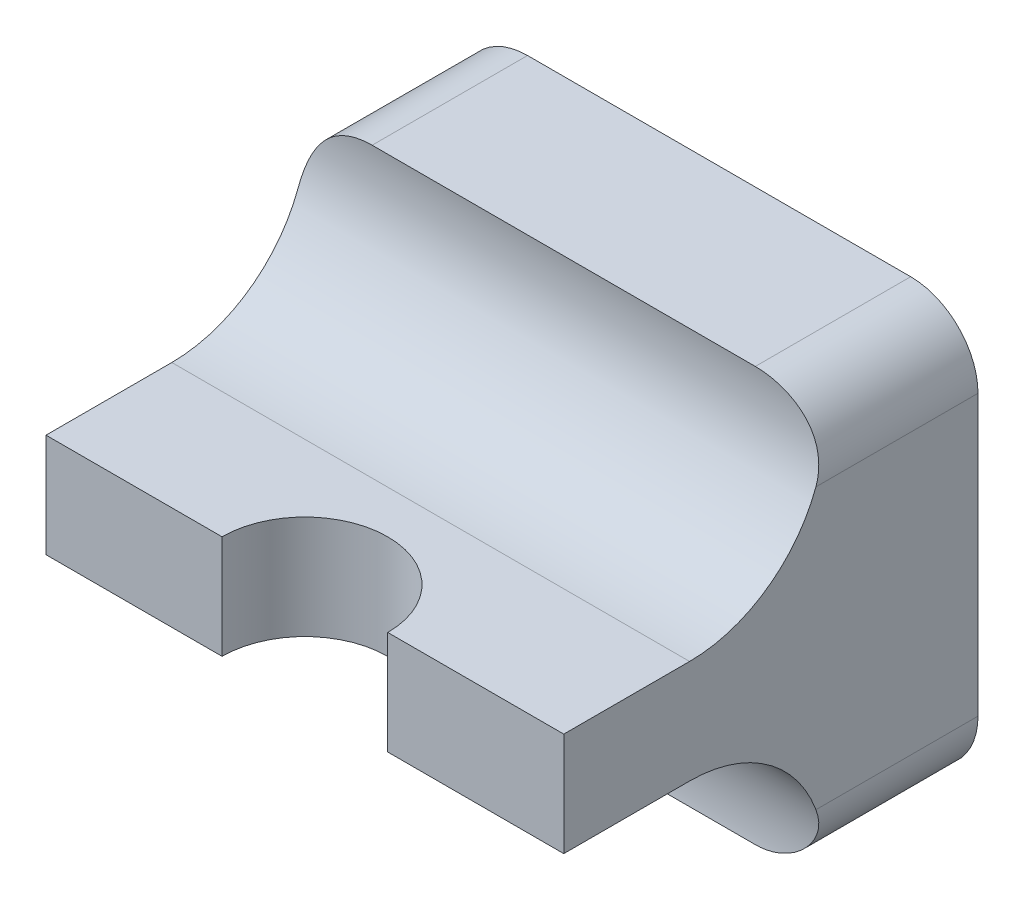
SolidWorks part; units mm, degrees
ref_plane "Front Plane" through (0, 0, 0) normal (0, 0, 1) x (1, 0, 0)
ref_plane "Top Plane" through (0, 0, 0) normal (0, 1, 0) x (1, 0, 0)
ref_plane "Right Plane" through (0, 0, 0) normal (1, 0, 0) x (0, 0, -1)
sketch "Sketch1" plane through (0, 0, 0) normal (0, 0, 1) x (1, 0, 0)
  line L9 (-37, -6.5) -> (0, -6.5)
  line L10 (-43.5, 0) -> (-43.5, 27)
  line L11 (-37, 33.5) -> (0, 33.5)
  line L12 (6.5, 0) -> (6.5, 27)
  arc A4 (-37, 33.5) -> (-43.5, 27) centre (-37, 27) ccw
  arc A5 (-43.5, 0) -> (-37, -6.5) centre (-37, 0) ccw
  arc A6 (0, -6.5) -> (6.5, 0) centre (0, 0) ccw
  arc A7 (6.5, 27) -> (0, 33.5) centre (0, 27) ccw
  point P3 (0, 0)
  point P4 (-43.5, 7.2576)
  point P12 (-7.3381, 33.5)
  point P13 (-6.5, 6.5)
  dimension "D3" = 40
  dimension "D1" = 50
  dimension "D2" = 13
extrude "Boss-Extrude3" add sketch "Sketch1" along normal blind 40
sketch "Sketch3" plane through (6.5, 0, 0) normal (1, 0, 0) x (0, 0, -1)
  line L1 (-40, 0) -> (-40, 27) construction
  line L4 (-27.8501, 18.5) -> (-40, 18.5)
  line L5 (-40, 33.5) -> (0, 33.5) construction
  line L11 (-40, 18.5) -> (-40, 33.5)
  line L12 (-40, 33.5) -> (-15.0049, 33.5)
  line L13 (-40, 8.5) -> (-40, -6.5)
  line L14 (-27.8452, 8.5) -> (-40, 8.5)
  line L17 (-40, -6.5) -> (-15, -6.5)
  line L18 (-40, -6.5) -> (0, -6.5) construction
  arc A2 (-27.8501, 18.5) -> (-15.0049, 33.5) centre (-27.8501, 31.5) ccw
  arc A4 (-15, -6.5) -> (-27.8452, 8.5) centre (-27.8452, -4.5) ccw
  dimension "D4" = 26
  dimension "D1" = 24.9951
  dimension "D2" = 15
  dimension "D3" = 15
  dimension "D6" = 25
extrude "Cut-Extrude1" cut sketch "Sketch3" against normal through all contours A2 L12 L11 L4 | L17 A4 L14 L13
sketch "Sketch4" plane through (0, 18.5, 0) normal (0, 1, 0) x (1, 0, 0)
  line L0 (-43.5, -40) -> (6.5, -40) construction
  line L1 (-10.5, -40) -> (-26.5, -40)
  arc A0 (-10.5, -40) -> (-26.5, -40) centre (-18.5, -40) ccw
  dimension "D1" = 16
extrude "Cut-Extrude2" cut sketch "Sketch4" against normal blind 10 contours A0 L1
